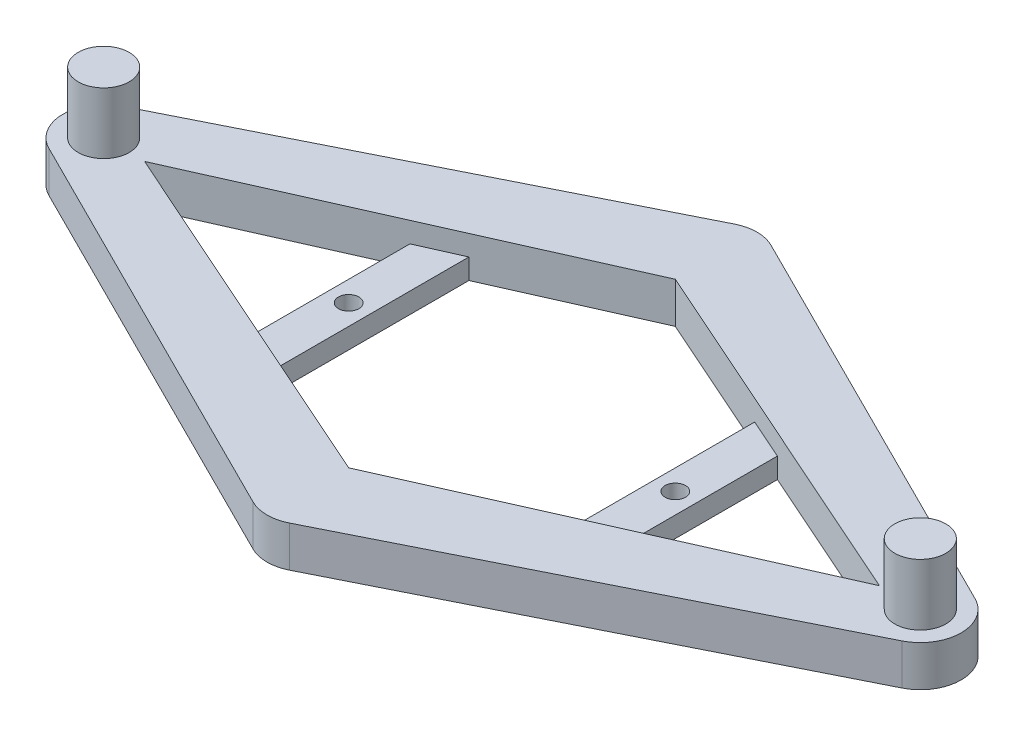
SolidWorks part; units mm, degrees
ref_plane "Front Plane" through (0, 0, 0) normal (0, 0, 1) x (1, 0, 0)
ref_plane "Top Plane" through (0, 0, 0) normal (0, 1, 0) x (1, 0, 0)
ref_plane "Right Plane" through (0, 0, 0) normal (1, 0, 0) x (0, 0, -1)
sketch "Sketch1" plane through (0, 0, 0) normal (0, 1, 0) x (1, 0, 0)
  line L0 (0, 0) -> (-50.8, 0)
  line L1 (0, 0) -> (50.8, 0)
  line L2 (0, 0) -> (0, 25.4)
  line L3 (0, 0) -> (0, -25.4)
  line L4 (-45.72, 0) -> (0, 20.32)
  line L5 (0, 20.32) -> (45.72, 0)
  line L6 (45.72, 0) -> (0, -20.32)
  line L7 (0, -20.32) -> (-45.72, 0)
  line L8 (-53.0718, -4.5437) -> (-2.2718, -29.9437)
  line L9 (-53.0718, 4.5437) -> (-2.2718, 29.9437)
  line L10 (2.2718, 29.9437) -> (53.0718, 4.5437)
  line L11 (53.0718, -4.5437) -> (2.2718, -29.9437)
  arc A0 (-53.0718, 4.5437) -> (-53.0718, -4.5437) centre (-50.8, 0) ccw
  arc A1 (2.2718, 29.9437) -> (-2.2718, 29.9437) centre (0, 25.4) ccw
  arc A2 (53.0718, -4.5437) -> (53.0718, 4.5437) centre (50.8, 0) ccw
  arc A3 (-2.2718, -29.9437) -> (2.2718, -29.9437) centre (0, -25.4) ccw
  dimension "D1" = 10.16
  dimension "D2" = 10.16
  dimension "D3" = 10.16
  dimension "D4" = 10.16
  dimension "D5" = 50.8
  dimension "D6" = 50.8
  dimension "D7" = 25.4
  dimension "D8" = 25.4
sketch "Sketch4" plane through (0, 0, 0) normal (0, 1, 0) x (1, 0, 0)
  line L0 (-22.86, 10.16) -> (-22.86, -10.16)
  line L1 (-45.72, 0) -> (0, 20.32) construction
  line L2 (0, -20.32) -> (-45.72, 0) construction
  line L3 (-22.86, 0) -> (-17.78, 0)
  line L4 (0, 0) -> (-50.8, 0) construction
  line L5 (-17.78, 0) -> (-17.78, 12.4178)
  line L6 (-17.78, 12.4178) -> (-17.78, -12.4178)
  line L7 (-22.86, 10.16) -> (-17.78, 12.4178)
  line L8 (-22.86, -10.16) -> (-17.78, -12.4178)
  line L9 (0, 20.32) -> (0, -20.32)
  line L10 (22.86, 10.16) -> (17.78, 12.4178)
  line L11 (22.86, 10.16) -> (22.86, -10.16)
  line L12 (22.86, -10.16) -> (17.78, -12.4178)
  line L13 (17.78, 12.4178) -> (17.78, -12.4178)
  circle A0 centre (-20.32, 0) radius 1.27
  circle A1 centre (20.32, 0) radius 1.27
sketch "Sketch5" plane through (0, 0, 0) normal (0, 1, 0) x (1, 0, 0)
  line L0 (-22.86, 10.16) -> (-22.86, -10.16)
  line L1 (-17.78, 12.4178) -> (-17.78, -12.4178)
  line L2 (-22.86, 10.16) -> (-17.78, 12.4178)
  line L3 (-22.86, -10.16) -> (-17.78, -12.4178)
  line L4 (22.86, 10.16) -> (17.78, 12.4178)
  line L5 (22.86, 10.16) -> (22.86, -10.16)
  line L6 (22.86, -10.16) -> (17.78, -12.4178)
  line L7 (17.78, 12.4178) -> (17.78, -12.4178)
  circle A0 centre (-20.32, 0) radius 1.27
  circle A1 centre (20.32, 0) radius 1.27
  point P2 (-22.86, 0)
extrude "Boss-Extrude2" add sketch "Sketch5" along normal blind 2.54
sketch "Sketch2" plane through (0, 0, 0) normal (0, 1, 0) x (1, 0, 0)
  line L0 (-45.72, 0) -> (0, 20.32)
  line L1 (0, 20.32) -> (45.72, 0)
  line L2 (45.72, 0) -> (0, -20.32)
  line L3 (0, -20.32) -> (-45.72, 0)
  line L4 (-53.0718, -4.5437) -> (-2.2718, -29.9437)
  line L5 (-53.0718, 4.5437) -> (-2.2718, 29.9437)
  line L6 (2.2718, 29.9437) -> (53.0718, 4.5437)
  line L7 (53.0718, -4.5437) -> (2.2718, -29.9437)
  arc A0 (-53.0718, 4.5437) -> (-53.0718, -4.5437) centre (-50.8, 0) ccw
  arc A1 (2.2718, 29.9437) -> (-2.2718, 29.9437) centre (0, 25.4) ccw
  arc A2 (53.0718, -4.5437) -> (53.0718, 4.5437) centre (50.8, 0) ccw
  arc A3 (-2.2718, -29.9437) -> (2.2718, -29.9437) centre (0, -25.4) ccw
extrude "Boss-Extrude1" add sketch "Sketch2" along normal blind 5.08
sketch "Sketch6" plane through (0, 5.08, 0) normal (0, 1, 0) x (1, 0, 0)
  circle A0 centre (-50.8, 0) radius 3.175
  circle A1 centre (50.8, 0) radius 3.175
extrude "Boss-Extrude3" add sketch "Sketch6" along normal blind 7.62
sketch "Sketch10" plane through (0, 12.7, 0) normal (0, 1, 0) x (1, 0, 0)
  circle A0 centre (-50.8, 0) radius 5.08
sketch "Sketch11" plane through (0, 12.7, 0) normal (0, 1, 0) x (1, 0, 0)
  circle A0 centre (-50.8, 0) radius 5.08
sketch "Sketch12" plane through (0, 12.7, 0) normal (0, 1, 0) x (1, 0, 0)
  circle A0 centre (50.8, 0) radius 5.08
sketch "Sketch13" plane through (0, 12.7, 0) normal (0, 1, 0) x (1, 0, 0)
  circle A0 centre (50.8, 0) radius 5.08
